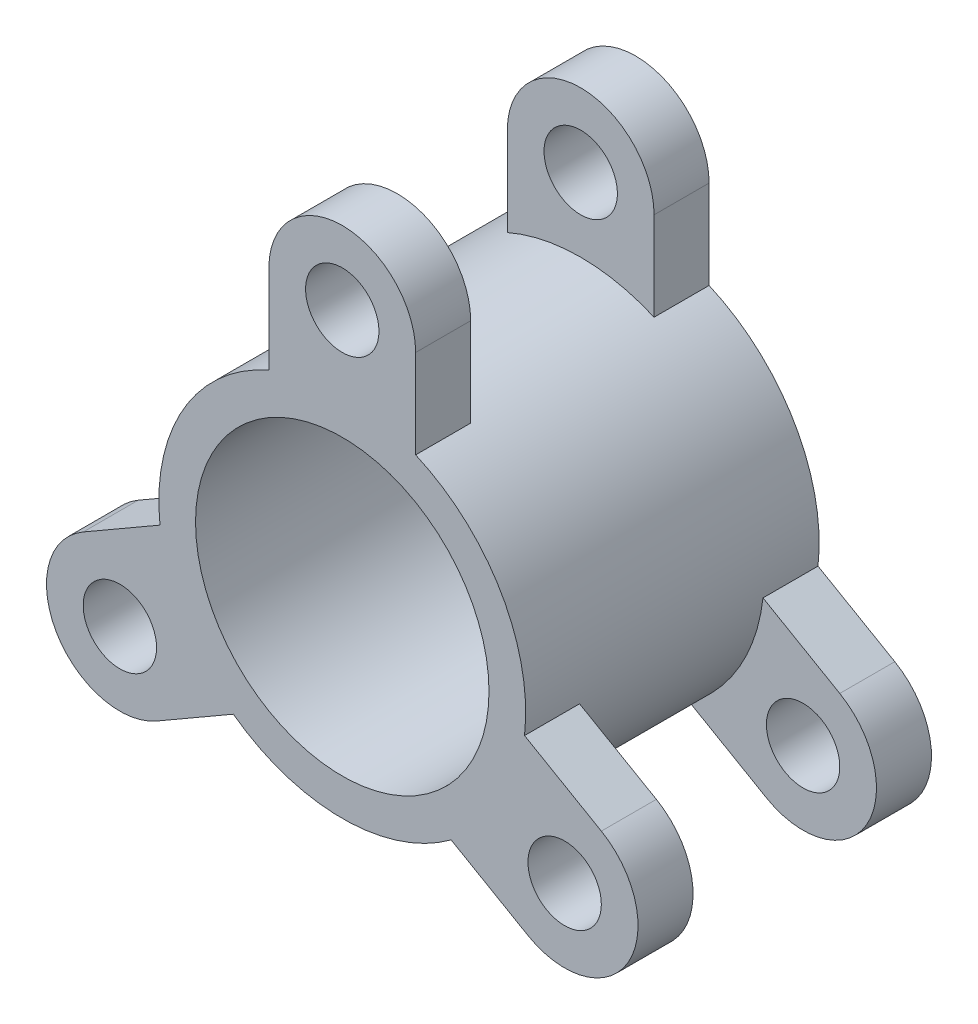
SolidWorks part; units mm, degrees
ref_plane "Front Plane" through (0, 0, 0) normal (0, 0, 1) x (1, 0, 0)
ref_plane "Top Plane" through (0, 0, 0) normal (0, 1, 0) x (1, 0, 0)
ref_plane "Right Plane" through (0, 0, 0) normal (1, 0, 0) x (0, 0, -1)
sketch "Sketch1" plane through (0, 0, 0) normal (0, 0, 1) x (1, 0, 0)
  line L0 (-20, 70) -> (-20, 45.8258)
  line L1 (0, 168.3207) -> (0, -127.4155) construction
  line L2 (-263.5773, 0) -> (259.9828, 0) construction
  line L3 (20, 70) -> (20, 45.8258)
  line L4 (70.6218, -17.6795) -> (49.6863, -5.5924)
  line L5 (50.6218, -52.3205) -> (29.6863, -40.2334)
  line L6 (-50.6218, -52.3205) -> (-29.6863, -40.2334)
  line L7 (-70.6218, -17.6795) -> (-49.6863, -5.5924)
  circle A0 centre (0, 0) radius 40
  circle A1 centre (0, 0) radius 50
  circle A2 centre (0, 0) radius 70 construction
  circle A3 centre (0, 70) radius 10
  arc A4 (20, 70) -> (-20, 70) centre (0, 70) ccw
  arc A5 (50.6218, -52.3205) -> (70.6218, -17.6795) centre (60.6218, -35) ccw
  circle A6 centre (60.6218, -35) radius 10
  arc A7 (-70.6218, -17.6795) -> (-50.6218, -52.3205) centre (-60.6218, -35) ccw
  circle A8 centre (-60.6218, -35) radius 10
  point P7 (0, 0)
  point P35 (0, 0)
  dimension "D1" = 100
  dimension "D2" = 80
  dimension "D3" = 140
  dimension "D4" = 20
  dimension "D5" = 40
  dimension "D6" = 3
extrude "Boss-Extrude1" add sketch "Sketch1" along normal blind 80 contours A1 A0 | L3 A4 L0 A1 A3 | L7 A7 L6 A1 A8 | L5 A5 L4 A1 A6
ref_axis "Axis1" through (0, 0, 80) along (0, 0, -1)
ref_plane "Plane2" through (0, 0, 0) normal (0.5, -0.866, 0) x (-0.866, -0.5, 0)
sketch "Sketch6" plane through (0, 0, 0) normal (0.5, -0.866, 0) x (-0.866, -0.5, 0)
  line L0 (50, -15) -> (50, -65)
  line L1 (50, -65) -> (110, -65)
  line L2 (110, -65) -> (110, -15)
  line L3 (110, -15) -> (50, -15)
  line L4 (0, -80) -> (0, 0) construction
  dimension "D1" = 50
  dimension "D2" = 50
  dimension "D3" = 60
  dimension "D4" = 15
revolve "Cut-Revolve1" cut sketch "Sketch6" angle 360 about axis through (0, 0, 80) along (0, 0, -1)
